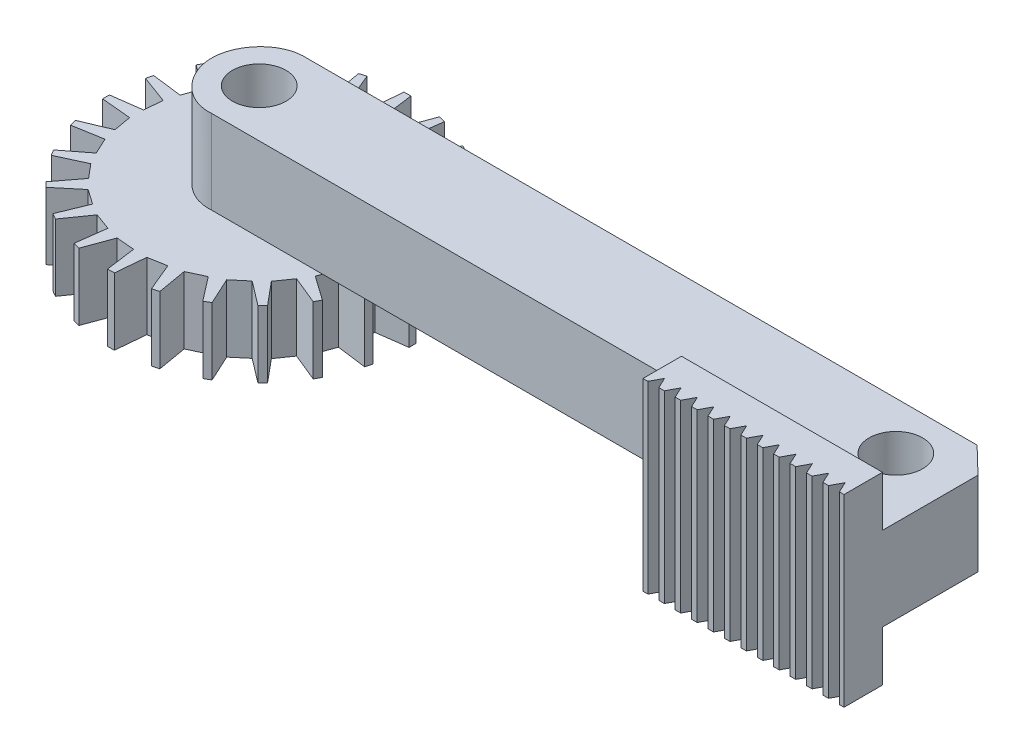
SolidWorks part; units mm, degrees
ref_plane "Plan de face" through (0, 0, 0) normal (0, 0, 1) x (1, 0, 0)
ref_plane "Plan de dessus" through (0, 0, 0) normal (0, 1, 0) x (1, 0, 0)
ref_plane "Plan de droite" through (0, 0, 0) normal (1, 0, 0) x (0, 0, -1)
sketch "Esquisse1" plane through (0, 0, 0) normal (0, 1, 0) x (1, 0, 0)
  circle A0 centre (0, 0) radius 9
  dimension "D1" = 18
extrude "Boss.-Extru.1" add sketch "Esquisse1" along normal blind 4
sketch "Esquisse2" plane through (0, 4, 0) normal (0, 1, 0) x (1, 0, 0)
  line L0 (0, 2.85) -> (28, 2.85)
  line L1 (0, -6.05) -> (0, 6.05) construction
  line L2 (-6.05, 0) -> (6.05, 0) construction
  line L3 (0, -2.85) -> (28, -2.85)
  line L6 (28, 2.85) -> (40, 2.85)
  line L24 (41.5825, 1.3218) -> (40, 2.85)
  line L25 (28, -2.85) -> (29.5825, -4.3782)
  line L26 (41.5825, 1.3218) -> (41.5825, -6.6782)
  line L27 (29.5825, -4.3782) -> (29.5825, -6.6782)
  line L28 (29.5825, -6.6782) -> (41.5825, -6.6782)
  circle A0 centre (0, 0) radius 2.8551 construction
  spline S0 degree 3 poles (0, 2.85) (-1.5838, 2.9448) (-4.1464, 0.0144) (-1.5439, -2.9663) (0, -2.85) knots 0 0 0 0 0.500312 1 1 1 1
  dimension "D1" = 5.7
  dimension "D2" = 28
  dimension "D3" = 12
  dimension "D4" = 2.2
  dimension "D5" = 136
  dimension "D6" = 8
extrude "Boss.-Extru.2" add sketch "Esquisse2" along normal blind 5
sketch "Esquisse3" plane through (0, 0, 0) normal (0, -1, 0) x (1, 0, 0)
  line L0 (0.3514, 8.9931) -> (0.5134, 7.2218)
  line L1 (0.5134, 7.2218) -> (1.5773, 7.0341)
  line L2 (1.5773, 7.0341) -> (2.2766, 8.7073)
  line L3 (2.2766, 8.7073) -> (1.4168, 9.583)
  line L4 (1.4168, 9.583) -> (0.3514, 8.9931)
  line L5 (3.3441, 6.3862) -> (4.4526, 7.8214)
  line L6 (2.3651, 6.8429) -> (3.3441, 6.3862)
  line L7 (2.6671, 8.5957) -> (2.3651, 6.8429)
  line L8 (3.8488, 8.8897) -> (2.6671, 8.5957)
  line L9 (4.4526, 7.8214) -> (3.8488, 8.8897)
  line L10 (4.883, 5.3031) -> (6.3252, 6.4024)
  line L11 (4.0556, 5.9976) -> (4.883, 5.3031)
  line L12 (4.8009, 7.6126) -> (4.0556, 5.9976)
  line L13 (6.0185, 7.5907) -> (4.8009, 7.6126)
  line L14 (6.3252, 6.4024) -> (6.0185, 7.5907)
  line L15 (6.0892, 3.8585) -> (7.7668, 4.5472)
  line L16 (5.4697, 4.7436) -> (6.0892, 3.8585)
  line L17 (6.6076, 6.1106) -> (5.4697, 4.7436)
  line L18 (7.778, 5.7743) -> (6.6076, 6.1106)
  line L19 (7.7668, 4.5472) -> (7.778, 5.7743)
  line L20 (6.8804, 2.1511) -> (8.679, 2.3821)
  line L21 (6.511, 3.1663) -> (6.8804, 2.1511)
  line L22 (7.964, 4.1922) -> (6.511, 3.1663)
  line L23 (9.0075, 3.5645) -> (7.964, 4.1922)
  line L24 (8.679, 2.3821) -> (9.0075, 3.5645)
  line L25 (7.2027, 0.297) -> (8.9998, 0.0546)
  line L26 (7.1087, 1.3732) -> (7.2027, 0.297)
  line L27 (8.7777, 1.9881) -> (7.1087, 1.3732)
  line L28 (9.6231, 1.1117) -> (8.7777, 1.9881)
  line L29 (8.9998, 0.0546) -> (9.6231, 1.1117)
  line L30 (7.0341, -1.5773) -> (8.7073, -2.2766)
  line L31 (7.2218, -0.5134) -> (7.0341, -1.5773)
  line L32 (8.9931, -0.3514) -> (7.2218, -0.5134)
  line L33 (9.583, -1.4168) -> (8.9931, -0.3514)
  line L34 (8.7073, -2.2766) -> (9.583, -1.4168)
  line L35 (6.3862, -3.3441) -> (7.8214, -4.4526)
  line L36 (6.8429, -2.3651) -> (6.3862, -3.3441)
  line L37 (8.5957, -2.6671) -> (6.8429, -2.3651)
  line L38 (8.8897, -3.8488) -> (8.5957, -2.6671)
  line L39 (7.8214, -4.4526) -> (8.8897, -3.8488)
  line L40 (5.3031, -4.883) -> (6.4024, -6.3252)
  line L41 (5.9976, -4.0556) -> (5.3031, -4.883)
  line L42 (7.6126, -4.8009) -> (5.9976, -4.0556)
  line L43 (7.5907, -6.0185) -> (7.6126, -4.8009)
  line L44 (6.4024, -6.3252) -> (7.5907, -6.0185)
  line L45 (3.8585, -6.0892) -> (4.5472, -7.7668)
  line L46 (4.7436, -5.4697) -> (3.8585, -6.0892)
  line L47 (6.1106, -6.6076) -> (4.7436, -5.4697)
  line L48 (5.7743, -7.778) -> (6.1106, -6.6076)
  line L49 (4.5472, -7.7668) -> (5.7743, -7.778)
  line L50 (2.1511, -6.8804) -> (2.3821, -8.679)
  line L51 (3.1663, -6.511) -> (2.1511, -6.8804)
  line L52 (4.1922, -7.964) -> (3.1663, -6.511)
  line L53 (3.5645, -9.0075) -> (4.1922, -7.964)
  line L54 (2.3821, -8.679) -> (3.5645, -9.0075)
  line L55 (0.297, -7.2027) -> (0.0546, -8.9998)
  line L56 (1.3732, -7.1087) -> (0.297, -7.2027)
  line L57 (1.9881, -8.7777) -> (1.3732, -7.1087)
  line L58 (1.1117, -9.6231) -> (1.9881, -8.7777)
  line L59 (0.0546, -8.9998) -> (1.1117, -9.6231)
  line L60 (-1.5773, -7.0341) -> (-2.2766, -8.7073)
  line L61 (-0.5134, -7.2218) -> (-1.5773, -7.0341)
  line L62 (-0.3514, -8.9931) -> (-0.5134, -7.2218)
  line L63 (-1.4168, -9.583) -> (-0.3514, -8.9931)
  line L64 (-2.2766, -8.7073) -> (-1.4168, -9.583)
  line L65 (-3.3441, -6.3862) -> (-4.4526, -7.8214)
  line L66 (-2.3651, -6.8429) -> (-3.3441, -6.3862)
  line L67 (-2.6671, -8.5957) -> (-2.3651, -6.8429)
  line L68 (-3.8488, -8.8897) -> (-2.6671, -8.5957)
  line L69 (-4.4526, -7.8214) -> (-3.8488, -8.8897)
  line L70 (-4.883, -5.3031) -> (-6.3252, -6.4024)
  line L71 (-4.0556, -5.9976) -> (-4.883, -5.3031)
  line L72 (-4.8009, -7.6126) -> (-4.0556, -5.9976)
  line L73 (-6.0185, -7.5907) -> (-4.8009, -7.6126)
  line L74 (-6.3252, -6.4024) -> (-6.0185, -7.5907)
  line L75 (-6.0892, -3.8585) -> (-7.7668, -4.5472)
  line L76 (-5.4697, -4.7436) -> (-6.0892, -3.8585)
  line L77 (-6.6076, -6.1106) -> (-5.4697, -4.7436)
  line L78 (-7.778, -5.7743) -> (-6.6076, -6.1106)
  line L79 (-7.7668, -4.5472) -> (-7.778, -5.7743)
  line L80 (-6.8804, -2.1511) -> (-8.679, -2.3821)
  line L81 (-6.511, -3.1663) -> (-6.8804, -2.1511)
  line L82 (-7.964, -4.1922) -> (-6.511, -3.1663)
  line L83 (-9.0075, -3.5645) -> (-7.964, -4.1922)
  line L84 (-8.679, -2.3821) -> (-9.0075, -3.5645)
  line L85 (-7.2027, -0.297) -> (-8.9998, -0.0546)
  line L86 (-7.1087, -1.3732) -> (-7.2027, -0.297)
  line L87 (-8.7777, -1.9881) -> (-7.1087, -1.3732)
  line L88 (-9.6231, -1.1117) -> (-8.7777, -1.9881)
  line L89 (-8.9998, -0.0546) -> (-9.6231, -1.1117)
  line L90 (-7.0341, 1.5773) -> (-8.7073, 2.2766)
  line L91 (-7.2218, 0.5134) -> (-7.0341, 1.5773)
  line L92 (-8.9931, 0.3514) -> (-7.2218, 0.5134)
  line L93 (-9.583, 1.4168) -> (-8.9931, 0.3514)
  line L94 (-8.7073, 2.2766) -> (-9.583, 1.4168)
  line L95 (-6.3862, 3.3441) -> (-7.8214, 4.4526)
  line L96 (-6.8429, 2.3651) -> (-6.3862, 3.3441)
  line L97 (-8.5957, 2.6671) -> (-6.8429, 2.3651)
  line L98 (-8.8897, 3.8488) -> (-8.5957, 2.6671)
  line L99 (-7.8214, 4.4526) -> (-8.8897, 3.8488)
  line L100 (-5.3031, 4.883) -> (-6.4024, 6.3252)
  line L101 (-5.9976, 4.0556) -> (-5.3031, 4.883)
  line L102 (-7.6126, 4.8009) -> (-5.9976, 4.0556)
  line L103 (-7.5907, 6.0185) -> (-7.6126, 4.8009)
  line L104 (-6.4024, 6.3252) -> (-7.5907, 6.0185)
  line L105 (-3.8585, 6.0892) -> (-4.5472, 7.7668)
  line L106 (-4.7436, 5.4697) -> (-3.8585, 6.0892)
  line L107 (-6.1106, 6.6076) -> (-4.7436, 5.4697)
  line L108 (-5.7743, 7.778) -> (-6.1106, 6.6076)
  line L109 (-4.5472, 7.7668) -> (-5.7743, 7.778)
  line L110 (-2.1511, 6.8804) -> (-2.3821, 8.679)
  line L111 (-3.1663, 6.511) -> (-2.1511, 6.8804)
  line L112 (-4.1922, 7.964) -> (-3.1663, 6.511)
  line L113 (-3.5645, 9.0075) -> (-4.1922, 7.964)
  line L114 (-2.3821, 8.679) -> (-3.5645, 9.0075)
  line L115 (-0.297, 7.2027) -> (-0.0546, 8.9998)
  line L116 (-1.3732, 7.1087) -> (-0.297, 7.2027)
  line L117 (-1.9881, 8.7777) -> (-1.3732, 7.1087)
  line L118 (-1.1117, 9.6231) -> (-1.9881, 8.7777)
  line L119 (-0.0546, 8.9998) -> (-1.1117, 9.6231)
  circle A0 centre (0, 0) radius 9 construction
  dimension "D1" = 24
extrude "Enlèv. mat.-Extru.1" cut sketch "Esquisse3" against normal blind 4
sketch "Esquisse4" plane through (0, 9, 0) normal (0, 1, 0) x (1, 0, 0)
  circle A0 centre (0, 0) radius 1.6
  dimension "D1" = 3.2
extrude "Enlèv. mat.-Extru.2" cut sketch "Esquisse4" against normal blind 12 and the other way blind 3
sketch "Esquisse5" plane through (0, 9, 0) normal (0, 1, 0) x (1, 0, 0)
  line L0 (29.5825, -6.6782) -> (29.5825, -4.3782)
  line L1 (29.5825, -4.3782) -> (41.5825, -4.3782)
  line L2 (41.5825, -6.6782) -> (41.5825, 1.3218) construction
  line L3 (41.5825, -4.3782) -> (41.5825, -6.6782)
  line L4 (41.5825, -6.6782) -> (29.5825, -6.6782)
extrude "Boss.-Extru.3" add sketch "Esquisse5" along normal blind 3 and the other way blind 8
sketch "Esquisse6" plane through (0, 12, 0) normal (0, 1, 0) x (1, 0, 0)
  line L0 (41.3073, -6.6782) -> (41.0047, -6.0282)
  line L1 (29.5825, -6.6782) -> (41.5825, -6.6782) construction
  line L2 (41.0047, -6.0282) -> (40.6573, -6.6782)
  line L3 (40.6573, -6.6782) -> (41.0047, -7.0308)
  line L4 (41.0047, -7.0308) -> (41.3073, -6.6782)
  line L5 (40.3273, -6.6782) -> (40.0247, -6.0282)
  line L6 (40.0247, -6.0282) -> (39.6773, -6.6782)
  line L7 (39.6773, -6.6782) -> (40.0247, -7.0308)
  line L8 (40.0247, -7.0308) -> (40.3273, -6.6782)
  line L9 (39.3473, -6.6782) -> (39.0447, -6.0282)
  line L10 (39.0447, -6.0282) -> (38.6973, -6.6782)
  line L11 (38.6973, -6.6782) -> (39.0447, -7.0308)
  line L12 (39.0447, -7.0308) -> (39.3473, -6.6782)
  line L13 (38.3673, -6.6782) -> (38.0647, -6.0282)
  line L14 (38.0647, -6.0282) -> (37.7173, -6.6782)
  line L15 (37.7173, -6.6782) -> (38.0647, -7.0308)
  line L16 (38.0647, -7.0308) -> (38.3673, -6.6782)
  line L17 (37.3873, -6.6782) -> (37.0847, -6.0282)
  line L18 (37.0847, -6.0282) -> (36.7373, -6.6782)
  line L19 (36.7373, -6.6782) -> (37.0847, -7.0308)
  line L20 (37.0847, -7.0308) -> (37.3873, -6.6782)
  line L21 (36.4073, -6.6782) -> (36.1047, -6.0282)
  line L22 (36.1047, -6.0282) -> (35.7573, -6.6782)
  line L23 (35.7573, -6.6782) -> (36.1047, -7.0308)
  line L24 (36.1047, -7.0308) -> (36.4073, -6.6782)
  line L25 (35.4273, -6.6782) -> (35.1247, -6.0282)
  line L26 (35.1247, -6.0282) -> (34.7773, -6.6782)
  line L27 (34.7773, -6.6782) -> (35.1247, -7.0308)
  line L28 (35.1247, -7.0308) -> (35.4273, -6.6782)
  line L29 (34.4473, -6.6782) -> (34.1447, -6.0282)
  line L30 (34.1447, -6.0282) -> (33.7973, -6.6782)
  line L31 (33.7973, -6.6782) -> (34.1447, -7.0308)
  line L32 (34.1447, -7.0308) -> (34.4473, -6.6782)
  line L33 (33.4673, -6.6782) -> (33.1647, -6.0282)
  line L34 (33.1647, -6.0282) -> (32.8173, -6.6782)
  line L35 (32.8173, -6.6782) -> (33.1647, -7.0308)
  line L36 (33.1647, -7.0308) -> (33.4673, -6.6782)
  line L37 (32.4873, -6.6782) -> (32.1847, -6.0282)
  line L38 (32.1847, -6.0282) -> (31.8373, -6.6782)
  line L39 (31.8373, -6.6782) -> (32.1847, -7.0308)
  line L40 (32.1847, -7.0308) -> (32.4873, -6.6782)
  line L41 (31.5073, -6.6782) -> (31.2047, -6.0282)
  line L42 (31.2047, -6.0282) -> (30.8573, -6.6782)
  line L43 (30.8573, -6.6782) -> (31.2047, -7.0308)
  line L44 (31.2047, -7.0308) -> (31.5073, -6.6782)
  line L45 (30.5273, -6.6782) -> (30.2247, -6.0282)
  line L46 (30.2247, -6.0282) -> (29.8773, -6.6782)
  line L47 (29.8773, -6.6782) -> (30.2247, -7.0308)
  line L48 (30.2247, -7.0308) -> (30.5273, -6.6782)
  dimension "D1" = 0.65
  dimension "D2" = 0.65
  dimension "D3" = 12
extrude "Enlèv. mat.-Extru.3" cut sketch "Esquisse6" against normal blind 11
sketch "Esquisse7" plane through (0, 9, 0) normal (0, 1, 0) x (1, 0, 0)
  line L0 (-4.95, 0) -> (4.95, 0) construction
  circle A0 centre (38, 0) radius 1.6
  dimension "D1" = 3.2
  dimension "D2" = 38
extrude "Enlèv. mat.-Extru.4" cut sketch "Esquisse7" against normal blind 11
